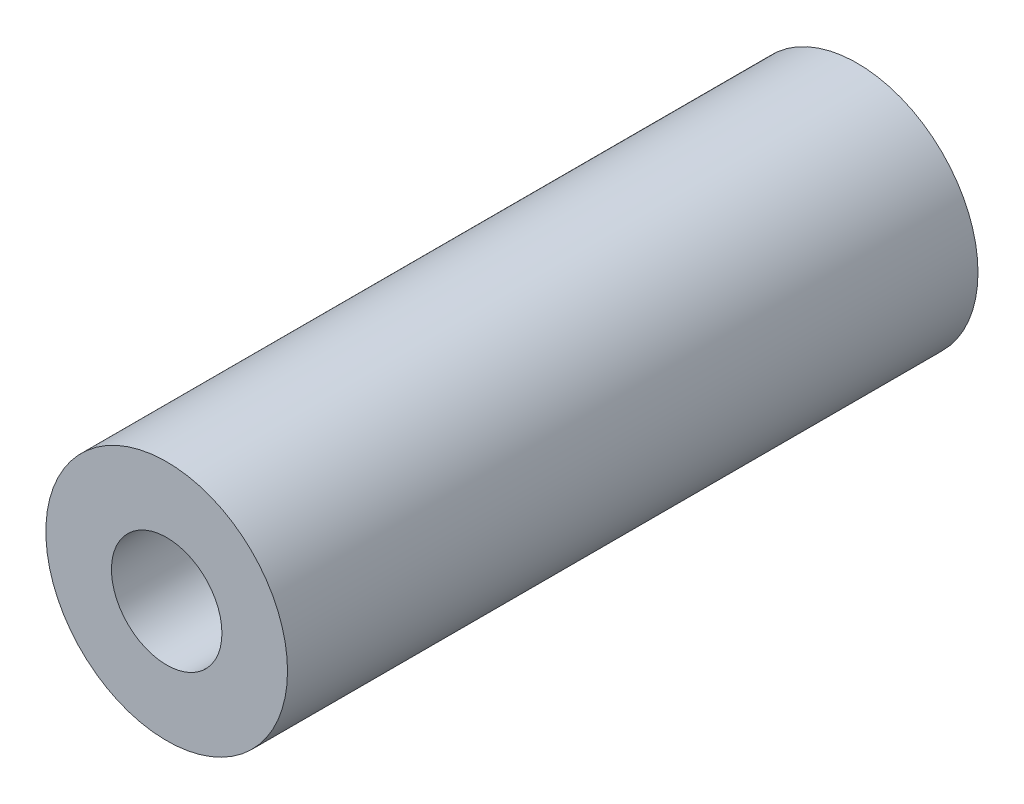
SolidWorks part; units mm, degrees
ref_plane "Front Plane" through (0, 0, 0) normal (0, 0, 1) x (1, 0, 0)
ref_plane "Top Plane" through (0, 0, 0) normal (0, 1, 0) x (1, 0, 0)
ref_plane "Right Plane" through (0, 0, 0) normal (1, 0, 0) x (0, 0, -1)
sketch "Sketch1" plane through (0, 0, 0) normal (0, 0, 1) x (1, 0, 0)
  circle A0 centre (0, 0) radius 3.5
  circle A1 centre (0, 0) radius 1.6
  dimension "D1" = 7
  dimension "D2" = 3.2
extrude "Boss-Extrude1" add sketch "Sketch1" along normal blind 20
equation "\"L1\"= 120mm'Upper arm"
equation "\"L3\"= 75mm'Wrist→TCP"
equation "\"h0\"= 75mm'Shoulder height"
equation "\"t_link\"= 3mm'Link plate thickness"
equation "\"t_bracket\"= 4mm'Bracket thickness"
equation "\"d_pin\"= 4mm'Pin diameter (M4)"
equation "\"c_fit\"= 0.2mm'Nominal clearance - measured PLA 2026-10-01"
equation "\"L2\"= 120mm'Forearm"
equation "\"c_fit_pivot\"= \"c_fit\" + 0.05mm'Gripper pivot clearance - chosen 0.25 mm 2026-10-01"
equation "\"d_pin_gripper\"= 3mm'Gripper pivot diameter"
equation "\"w_link\"= 20mm'Link plate depth (bending direction)"
equation "\"w_gap\"= 20mm'Twin-plate gap - provisional, set by elbow servo mount"
equation "\"d_boss\"= 13mm'MG996R output boss dia - from downloaded model, verify with calipers"
equation "\"c_boss\"= 1mm'Radial clearance around servo boss"
equation "\"d_servo_hole\"= \"d_boss\" + 2 * \"c_boss\"'Plate clearance hole for servo boss (15 mm)"
equation "\"t_rim\"= 7.5mm'Min material around servo hole (M3 bolt ring + edge)"
equation "\"w_link_end\"= \"d_servo_hole\" + 2 * \"t_rim\"'Link plate end width at servo end (30 mm)"
equation "\"d_hole_m3\"= \"d_pin_gripper\" + \"c_fit\"'M3 bolt clearance hole (spacer and adapter bolts)"
equation "\"d_hole_pivot\"= \"d_pin\" + \"c_fit_pivot\"'M4 pivot hole where the pin rotates (4.25 mm)"
equation "\"D2@Sketch1\"=\"d_hole_m3\""
equation "\"D1@Boss-Extrude1\"=\"w_gap\""
